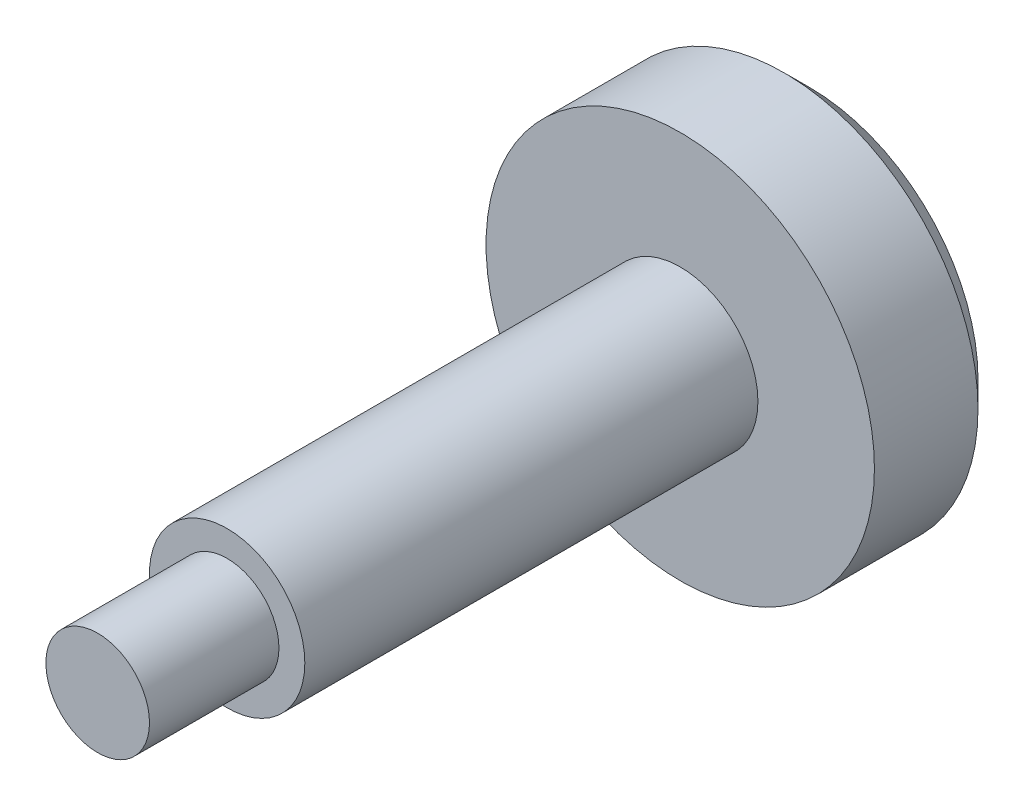
SolidWorks part; units mm, degrees
ref_plane "Plano frontal" through (0, 0, 0) normal (0, 0, 1) x (1, 0, 0)
ref_plane "Plano superior" through (0, 0, 0) normal (0, 1, 0) x (1, 0, 0)
ref_plane "Plano direito" through (0, 0, 0) normal (1, 0, 0) x (0, 0, -1)
sketch "Esboço1" plane through (0, 0, 0) normal (0, 0, 1) x (1, 0, 0)
  circle A0 centre (0, 0) radius 15
  dimension "D1" = 30
extrude "Ressalto-extrusão1" add sketch "Esboço1" along normal blind 10
sketch "Esboço2" plane through (0, 0, 10) normal (0, 0, 1) x (1, 0, 0)
  circle A0 centre (0, 0) radius 6
  dimension "D1" = 12
extrude "Ressalto-extrusão2" add sketch "Esboço2" along normal blind 35
sketch "Esboço3" plane through (0, 0, 45) normal (0, 0, 1) x (1, 0, 0)
  circle A0 centre (0, 0) radius 4
  dimension "D1" = 8
extrude "Ressalto-extrusão3" add sketch "Esboço3" along normal blind 10
chamfer "Chanfro1" distance 2 angle 45 1 edges at (15, 0, 0)
